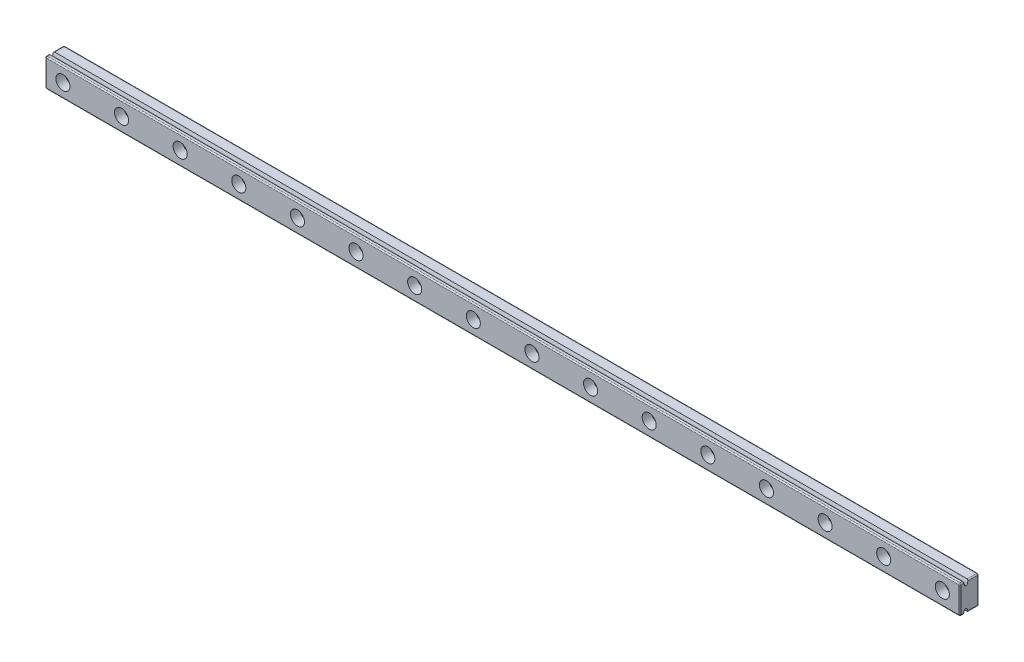
SolidWorks part; units mm, degrees
material "AISI 304"
ref_plane "Front Plane" through (0, 0, 0) normal (0, 0, 1) x (1, 0, 0)
ref_plane "Top Plane" through (0, 0, 0) normal (0, 1, 0) x (1, 0, 0)
ref_plane "Right Plane" through (0, 0, 0) normal (1, 0, 0) x (0, 0, -1)
sketch "Sketch1" plane through (0, 0, 0) normal (1, 0, 0) x (0, 0, -1)
  line L0 (-0.5, 6) -> (4, 6)
  line L1 (-4, 6) -> (-2.5, 6)
  line L2 (-4, 6) -> (-4, -6)
  line L3 (-4, -6) -> (-2.5, -6)
  line L4 (4, 6) -> (4, -6)
  line L5 (-4, 6) -> (4, -6) construction
  line L6 (-4, -6) -> (4, 6) construction
  line L8 (-2.5, 6) -> (-2.5, 4.25)
  line L9 (-2.5, 4.25) -> (-0.5, 4.25)
  line L10 (-0.5, 6) -> (-0.5, 4.25)
  line L12 (-2.5, -6) -> (-2.5, -4.25)
  line L13 (-2.5, -4.25) -> (-0.5, -4.25)
  line L14 (-0.5, -6) -> (-0.5, -4.25)
  line L15 (-0.5, -6) -> (4, -6)
  point P0 (0, 0)
  dimension "D1" = 12
  dimension "D2" = 8
  dimension "D3" = 2
  dimension "D4" = 2
  dimension "D5" = 1.5
  dimension "D6" = 1.5
  dimension "D7" = 8.5
  dimension "D8" = 4.25
extrude "Boss-Extrude1" add sketch "Sketch1" along normal blind 390
sketch "Sketch2" plane through (0, 0, 4) normal (0, 0, 1) x (1, 0, 0)
  line L0 (0, 6) -> (0, -6) construction
  line L1 (7.5, 0) -> (0, 0) construction
  circle A0 centre (7.5, 0) radius 1.75
  circle A1 centre (32.5, 0) radius 1.75
  circle A2 centre (57.5, 0) radius 1.75
  circle A3 centre (82.5, 0) radius 1.75
  circle A4 centre (107.5, 0) radius 1.75
  circle A5 centre (132.5, 0) radius 1.75
  circle A6 centre (157.5, 0) radius 1.75
  circle A7 centre (182.5, 0) radius 1.75
  circle A8 centre (207.5, 0) radius 1.75
  circle A9 centre (232.5, 0) radius 1.75
  circle A10 centre (257.5, 0) radius 1.75
  circle A11 centre (282.5, 0) radius 1.75
  circle A12 centre (307.5, 0) radius 1.75
  circle A13 centre (332.5, 0) radius 1.75
  circle A14 centre (357.5, 0) radius 1.75
  circle A15 centre (382.5, 0) radius 1.75
  dimension "D1" = 3.5
  dimension "D4" = 25
  dimension "D2" = 7.5
  dimension "D3" = 16
extrude "Cut-Extrude1" cut sketch "Sketch2" against normal blind 10
sketch "Sketch3" plane through (0, 0, 4) normal (0, 0, 1) x (1, 0, 0)
  circle A0 centre (7.5, 0) radius 3
  circle A1 centre (32.5, 0) radius 3
  circle A2 centre (57.5, 0) radius 3
  circle A3 centre (82.5, 0) radius 3
  circle A4 centre (107.5, 0) radius 3
  circle A5 centre (132.5, 0) radius 3
  circle A6 centre (157.5, 0) radius 3
  circle A7 centre (182.5, 0) radius 3
  circle A8 centre (207.5, 0) radius 3
  circle A9 centre (232.5, 0) radius 3
  circle A10 centre (257.5, 0) radius 3
  circle A11 centre (282.5, 0) radius 3
  circle A12 centre (307.5, 0) radius 3
  circle A13 centre (332.5, 0) radius 3
  circle A14 centre (357.5, 0) radius 3
  circle A15 centre (382.5, 0) radius 3
  dimension "D1" = 6
  dimension "D3" = 25
  dimension "D2" = 16
extrude "Cut-Extrude2" cut sketch "Sketch3" against normal blind 4
chamfer "Chamfer1" distance 0.5 angle 74 4 edges at (195, -4.25, 2.5) (195, -4.25, 0.5) (195, 4.25, 2.5) (195, 4.25, 0.5)
fillet "Fillet1" radius 0.5 20 edges at (390, -6, -1.75) (390, 0, -4) (390, 6, -1.75) (390, 6, 3.25) (390, 0, 4) (390, -6, 3.25) (0, -6, 3.25) (0, -6, -1.75) (0, 0, -4) (0, 6, -1.75) (0, 6, 3.25) (0, 0, 4) (195, -4.25, 1) (195, -4.25, 2) (195, 4.25, 2) (195, 4.25, 1) (195, -6, 4) (195, 6, 4) (195, -6, -4) (195, 6, -4)
